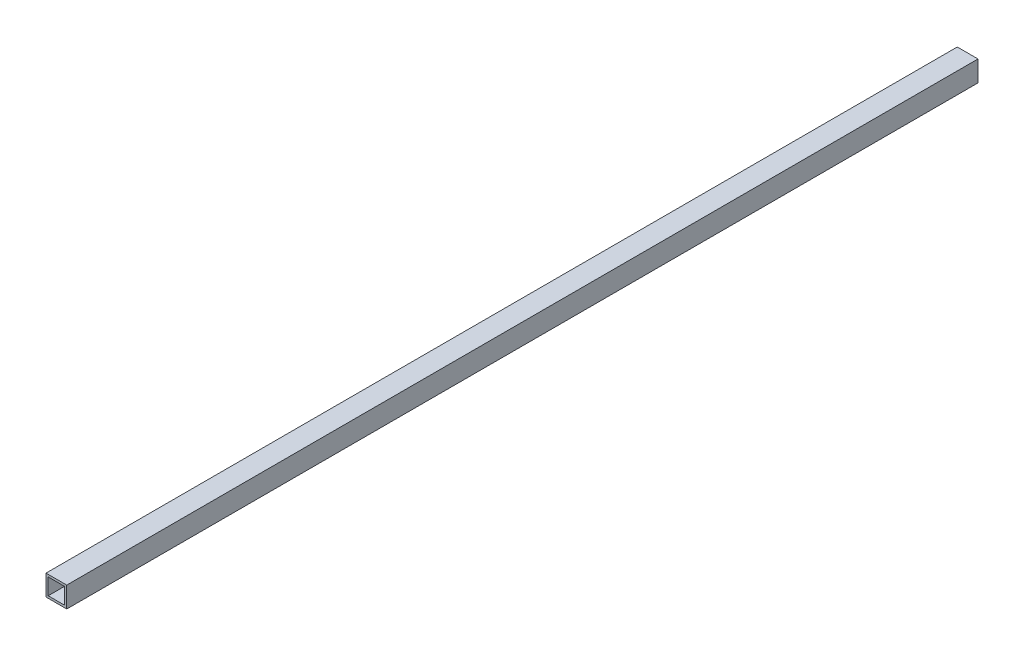
SolidWorks part; units mm, degrees
ref_plane "前视基准面" through (0, 0, 0) normal (0, 0, 1) x (1, 0, 0)
ref_plane "上视基准面" through (0, 0, 0) normal (0, 1, 0) x (1, 0, 0)
ref_plane "右视基准面" through (0, 0, 0) normal (1, 0, 0) x (0, 0, -1)
sketch "草图1" plane through (0, 0, 0) normal (0, 0, 1) x (1, 0, 0)
  line L1 (-5.5, 5.5) -> (5.5, 5.5)
  line L2 (-5.5, 5.5) -> (-5.5, -5.5)
  line L3 (-5.5, -5.5) -> (5.5, -5.5)
  line L4 (5.5, 5.5) -> (5.5, -5.5)
  line L5 (-5.5, 5.5) -> (5.5, -5.5) construction
  line L6 (-5.5, -5.5) -> (5.5, 5.5) construction
  point P0 (0, 0)
  dimension "D1" = 11
extrude "拉伸-薄壁1" add sketch "草图1" along normal blind 615 thin thin type one direction wall 1.5
